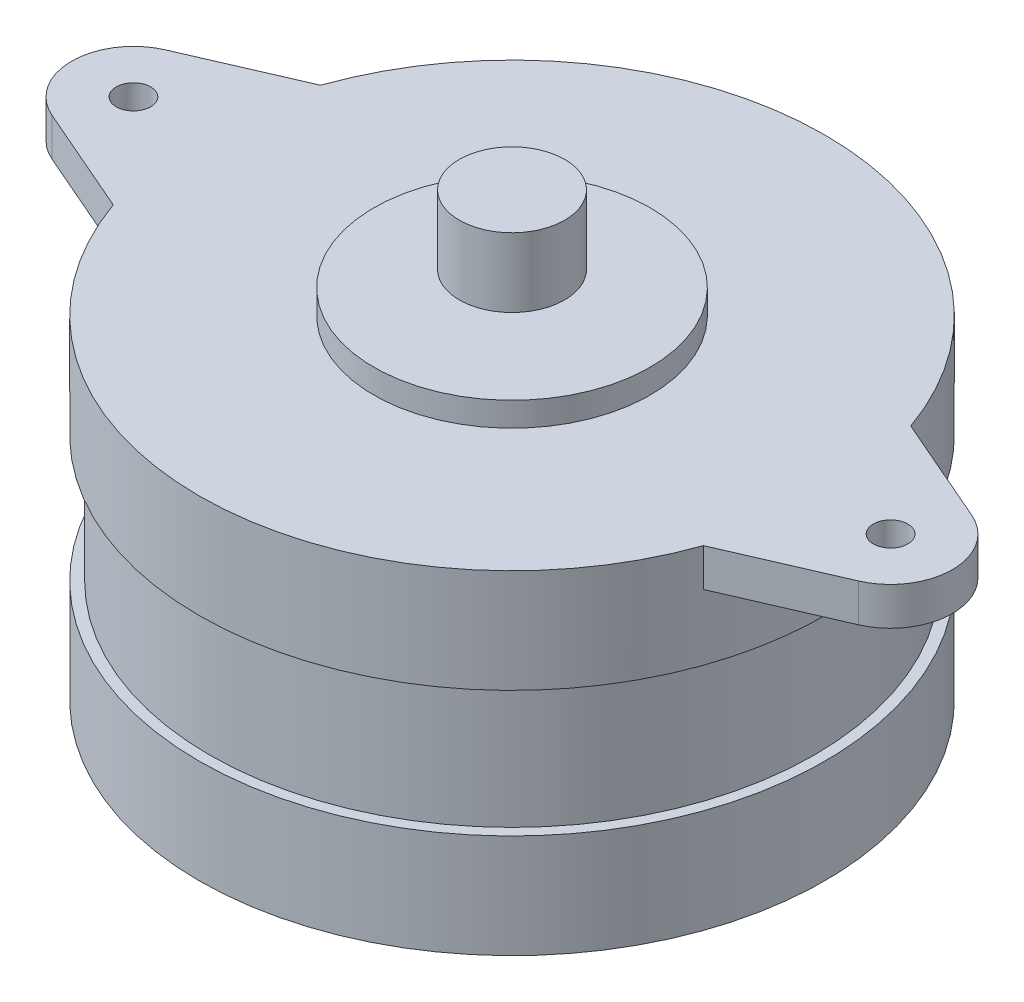
SolidWorks part; units mm, degrees
ref_plane "Front Plane" through (0, 0, 0) normal (0, 0, 1) x (1, 0, 0)
ref_plane "Top Plane" through (0, 0, 0) normal (0, 1, 0) x (1, 0, 0)
ref_plane "Right Plane" through (0, 0, 0) normal (1, 0, 0) x (0, 0, -1)
sketch "Sketch1" plane through (0, 0, 0) normal (0, 0, 1) x (1, 0, 0)
  line L0 (0, 0) -> (0, 25.6) construction
  line L1 (0, 25.6) -> (3.05, 25.6)
  line L2 (3.05, 25.6) -> (3.05, 21.6)
  line L3 (3.05, 21.6) -> (1.25, 21.6)
  line L4 (1.25, 21.6) -> (1.25, 20.7)
  line L5 (1.25, 20.7) -> (8, 20.7)
  line L6 (8, 20.7) -> (8, 19.3)
  line L7 (8, 19.3) -> (18.11, 19.3)
  line L8 (18.11, 19.3) -> (18.11, 13.3)
  line L9 (18.11, 13.3) -> (17.5, 13.3)
  line L10 (17.5, 13.3) -> (17.5, 6)
  line L11 (17.5, 6) -> (18.11, 6)
  line L12 (18.11, 6) -> (18.11, 0)
  line L13 (18.11, 0) -> (0, 0)
  line L14 (0, 0) -> (0, 25.6)
  dimension "D1" = 36.22
  dimension "D2" = 6
  dimension "D3" = 19.3
  dimension "D4" = 35
  dimension "D5" = 16
  dimension "D6" = 20.7
  dimension "D7" = 25.6
  dimension "D8" = 6.1
  dimension "D9" = 4
  dimension "D10" = 2.5
revolve "Revolve1" add sketch "Sketch1" angle 360 about L0
sketch "Sketch2" plane through (0, 19.3, 0) normal (0, 1, 0) x (1, 0, 0)
  line L0 (-21.92, 0) -> (21.92, 0) construction
  line L5 (-25.5, 0) -> (25.5, 0) construction
  line L6 (-23.3453, 3.2841) -> (-17.0872, 6)
  line L7 (-23.3453, -3.2841) -> (-17.0872, -6)
  line L8 (17.0872, 6) -> (23.3453, 3.2841)
  line L9 (17.0872, -6) -> (23.3453, -3.2841)
  circle A0 centre (-21.92, 0) radius 1
  circle A1 centre (21.92, 0) radius 1
  circle A2 centre (0, 0) radius 18.11 construction
  arc A3 (-17.0872, 6) -> (-17.0872, -6) centre (0, 0) ccw
  arc A4 (-23.3453, -3.2841) -> (-23.3453, 3.2841) centre (-21.92, 0) cw
  arc A5 (17.0872, -6) -> (17.0872, 6) centre (0, 0) ccw
  arc A6 (23.3453, 3.2841) -> (23.3453, -3.2841) centre (21.92, 0) cw
  point P7 (17.4291, -4.9191)
  point P11 (17.5527, 4.4581)
  point P19 (17.2725, -5.4436)
  point P20 (-16.8428, 6.6551)
  dimension "D1" = 2
  dimension "D3" = 51
  dimension "D2" = 43.84
  dimension "D4" = 12
extrude "Boss-Extrude1" add sketch "Sketch2" against normal blind 2.2
